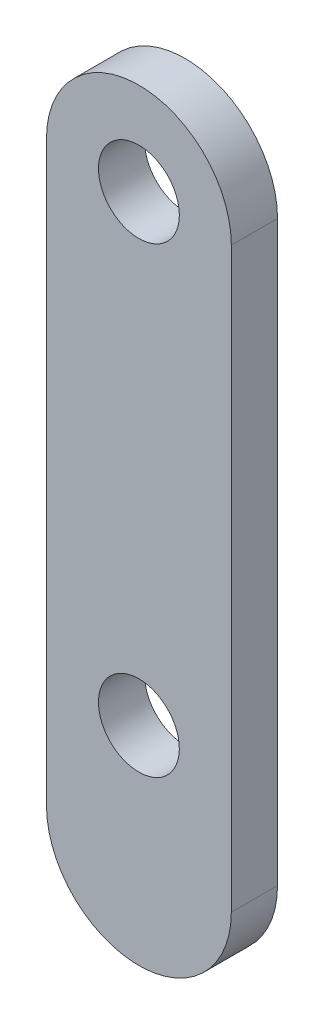
SolidWorks part; units mm, degrees
ref_plane "前视基准面" through (0, 0, 0) normal (0, 0, 1) x (1, 0, 0)
ref_plane "上视基准面" through (0, 0, 0) normal (0, 1, 0) x (1, 0, 0)
ref_plane "右视基准面" through (0, 0, 0) normal (1, 0, 0) x (0, 0, -1)
other "Configuration Table"
sketch "草图2" plane through (0, 0, 0) normal (0, 0, 1) x (1, 0, 0)
  line L0 (0, 0) -> (0, 25) construction
  line L1 (-4, 0) -> (-4, 25)
  line L2 (4, 0) -> (4, 25)
  arc A0 (-4, 0) -> (4, 0) centre (0, 0) ccw
  arc A1 (4, 25) -> (-4, 25) centre (0, 25) ccw
  circle A2 centre (0, 5) radius 1.75
  circle A3 centre (0, 25) radius 1.75
  point P3 (0, 12.5)
  dimension "D3" = 3.5
  dimension "D5" = 3.5
  dimension "D1" = 25
  dimension "D2" = 8
  dimension "D4" = 5
extrude "凸台-拉伸1" add sketch "草图2" along normal blind 2
